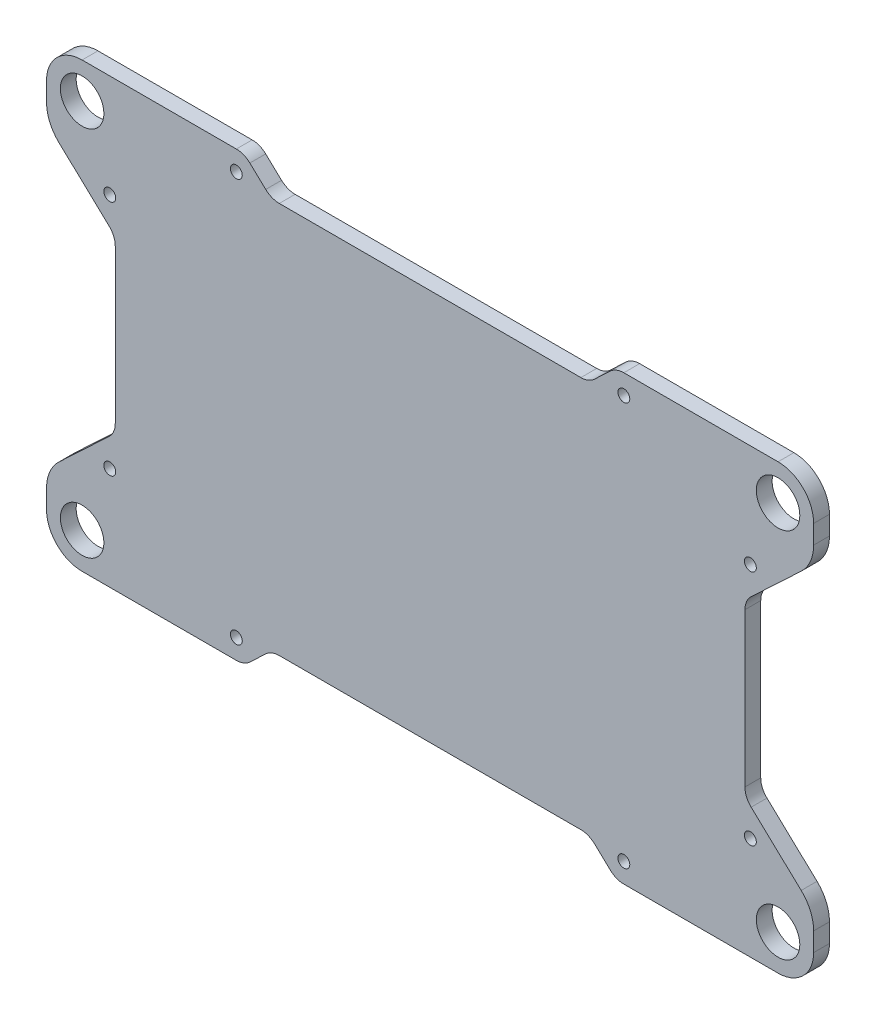
SolidWorks part; units mm, degrees
material "6061 Сплав"
ref_plane "Спереди" through (0, 0, 0) normal (0, 0, 1) x (1, 0, 0)
ref_plane "Сверху" through (0, 0, 0) normal (0, 1, 0) x (1, 0, 0)
ref_plane "Справа" through (0, 0, 0) normal (1, 0, 0) x (0, 0, -1)
other "Configuration Table"
sketch "Эскиз1" plane through (0, 0, 0) normal (0, 0, 1) x (1, 0, 0)
  line L0 (-1.4742, 68.0166) -> (-77.7465, 68.0166)
  line L2 (-136.6103, 65.5061) -> (-136.6103, 60.749)
  line L3 (-39.6103, -31.0045) -> (-39.6103, 68.0166) construction
  line L5 (40.0087, 18.5061) -> (-119.2293, 18.5061) construction
  line L7 (-127.6103, 74.5061) -> (-88.6103, 74.5061)
  line L8 (-85.1849, 73.1484) -> (-81.1719, 69.3743)
  line L9 (-133.4612, 53.4644) -> (-120.8039, 41.5606)
  line L10 (-119.2293, 37.9183) -> (-119.2293, -0.9062)
  line L11 (-133.4612, -16.4523) -> (-120.8039, -4.5485)
  line L12 (-85.1849, -36.1362) -> (-81.1719, -32.3622)
  line L13 (-127.6103, -37.4939) -> (-88.6103, -37.4939)
  line L14 (-136.6103, -28.4939) -> (-136.6103, -23.7369)
  line L15 (-1.4742, -31.0045) -> (-77.7465, -31.0045)
  line L16 (57.3897, -28.4939) -> (57.3897, -23.7369)
  line L17 (48.3897, -37.4939) -> (9.3897, -37.4939)
  line L18 (5.9642, -36.1362) -> (1.9513, -32.3622)
  line L19 (54.2406, -16.4523) -> (41.5832, -4.5485)
  line L20 (40.0087, 37.9183) -> (40.0087, -0.9062)
  line L21 (54.2406, 53.4644) -> (41.5832, 41.5606)
  line L22 (5.9642, 73.1484) -> (1.9513, 69.3743)
  line L23 (48.3897, 74.5061) -> (9.3897, 74.5061)
  line L24 (57.3897, 65.5061) -> (57.3897, 60.749)
  circle A0 centre (-88.6103, 69.5061) radius 1.5
  circle A1 centre (9.3897, 69.5061) radius 1.5
  circle A2 centre (41.3897, 48.5061) radius 1.5
  circle A3 centre (41.3897, -11.4939) radius 1.5
  circle A4 centre (9.3897, -32.4939) radius 1.5
  circle A5 centre (-88.6103, -32.4939) radius 1.5
  circle A6 centre (-120.6103, -11.4939) radius 1.5
  circle A7 centre (-120.6103, 48.5061) radius 1.5
  circle A8 centre (-127.6103, 65.5061) radius 5.5
  arc A9 (-127.6103, 74.5061) -> (-136.6103, 65.5061) centre (-127.6103, 65.5061) ccw
  arc A10 (-85.1849, 73.1484) -> (-88.6103, 74.5061) centre (-88.6103, 69.5061) ccw
  arc A11 (-136.6103, 60.749) -> (-133.4612, 53.4644) centre (-126.6103, 60.749) ccw
  arc A12 (-77.7465, 68.0166) -> (-81.1719, 69.3743) centre (-77.7465, 73.0166) cw
  arc A13 (-120.8039, 41.5606) -> (-119.2293, 37.9183) centre (-124.2293, 37.9183) cw
  arc A14 (-120.8039, -4.5485) -> (-119.2293, -0.9062) centre (-124.2293, -0.9062) ccw
  arc A15 (-77.7465, -31.0045) -> (-81.1719, -32.3622) centre (-77.7465, -36.0045) ccw
  arc A16 (-136.6103, -23.7369) -> (-133.4612, -16.4523) centre (-126.6103, -23.7369) cw
  arc A17 (-85.1849, -36.1362) -> (-88.6103, -37.4939) centre (-88.6103, -32.4939) cw
  arc A18 (-127.6103, -37.4939) -> (-136.6103, -28.4939) centre (-127.6103, -28.4939) cw
  circle A19 centre (-127.6103, -28.4939) radius 5.5
  circle A20 centre (-120.6103, -11.4939) radius 1.5
  circle A21 centre (-88.6103, -32.4939) radius 1.5
  circle A22 centre (9.3897, -32.4939) radius 1.5
  circle A23 centre (41.3897, -11.4939) radius 1.5
  circle A24 centre (48.3897, -28.4939) radius 5.5
  arc A25 (48.3897, -37.4939) -> (57.3897, -28.4939) centre (48.3897, -28.4939) ccw
  arc A26 (5.9642, -36.1362) -> (9.3897, -37.4939) centre (9.3897, -32.4939) ccw
  arc A27 (57.3897, -23.7369) -> (54.2406, -16.4523) centre (47.3897, -23.7369) ccw
  arc A28 (-1.4742, -31.0045) -> (1.9513, -32.3622) centre (-1.4742, -36.0045) cw
  arc A29 (41.5832, -4.5485) -> (40.0087, -0.9062) centre (45.0087, -0.9062) cw
  arc A30 (41.5832, 41.5606) -> (40.0087, 37.9183) centre (45.0087, 37.9183) ccw
  arc A31 (-1.4742, 68.0166) -> (1.9513, 69.3743) centre (-1.4742, 73.0166) ccw
  arc A32 (57.3897, 60.749) -> (54.2406, 53.4644) centre (47.3897, 60.749) cw
  arc A33 (5.9642, 73.1484) -> (9.3897, 74.5061) centre (9.3897, 69.5061) cw
  arc A34 (48.3897, 74.5061) -> (57.3897, 65.5061) centre (48.3897, 65.5061) cw
  circle A35 centre (48.3897, 65.5061) radius 5.5
  circle A36 centre (41.3897, 48.5061) radius 1.5
  circle A37 centre (41.3897, -11.4939) radius 1.5
  circle A38 centre (9.3897, -32.4939) radius 1.5
  circle A39 centre (9.3897, 69.5061) radius 1.5
  point P49 (-79.7283, 68.0166)
  point P52 (-119.2293, 40.0798)
  point P71 (-39.6103, 18.5061)
  point P107 (40.0087, 40.0798)
  point P108 (0.5076, 68.0166)
  dimension "D1" = 3
  dimension "D2" = 3
  dimension "D3" = 3
  dimension "D4" = 3
  dimension "D5" = 3
  dimension "D6" = 3
  dimension "D7" = 3
  dimension "D8" = 3
  dimension "D9" = 11
  dimension "D10" = 18
  dimension "D11" = 176
  dimension "D12" = 94
  dimension "D13" = 10
  dimension "D14" = 5
extrude "Бобышка-Вытянуть1" add sketch "Эскиз1" along normal blind 4 contours A34 L23 A33 L22 A31 L0 A12 L8 A10 L7 A9 L2 A11 L9 A13 L10 A14 L11 A16 L14 A18 L13 A17 L12 A15 L15 A28 L18 A26 L17 A25 L16 A27 L19 A29 L20 A30 L21 A32 L24 A19 A8 A7 A6 A5
